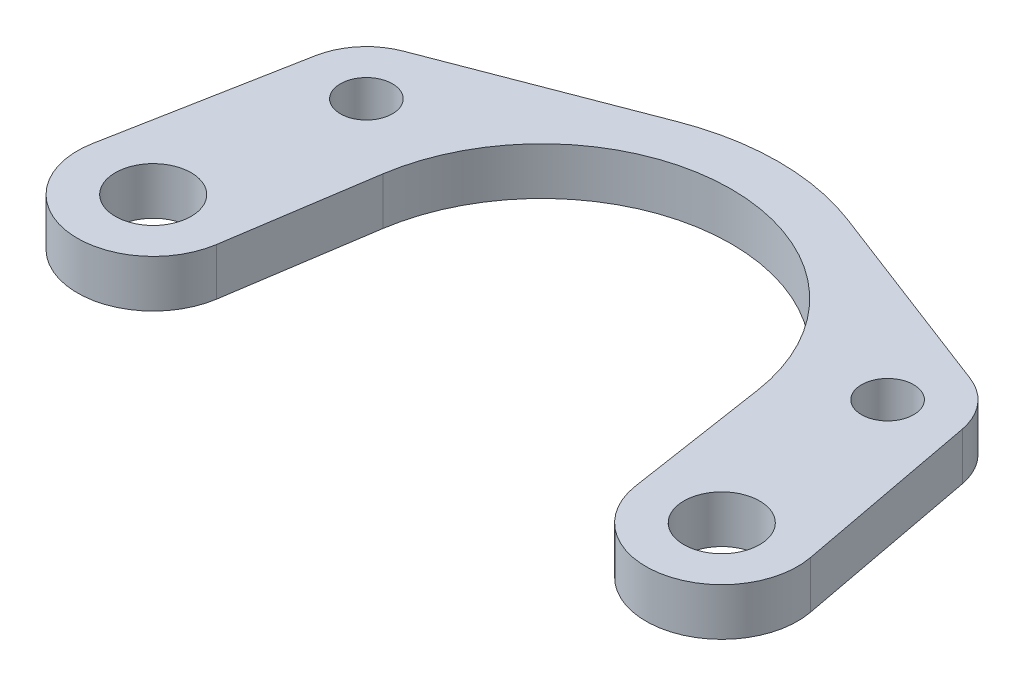
SolidWorks part; units mm, degrees
material "High-leaded brass, UNS C34200"
ref_plane "Front Plane" through (0, 0, 0) normal (0, 0, 1) x (1, 0, 0)
ref_plane "Top Plane" through (0, 0, 0) normal (0, 1, 0) x (1, 0, 0)
ref_plane "Right Plane" through (0, 0, 0) normal (1, 0, 0) x (0, 0, -1)
sketch "Sketch1" plane through (0, 0, 0) normal (0, 1, 0) x (1, 0, 0)
  line L0 (0, 25.4) -> (0, -25.4) construction
  line L1 (48.084, -12.087) -> (43.349, 13.0188)
  line L2 (28.056, -15.5009) -> (25.11, 3.8273)
  line L3 (11.3685, 29.6449) -> (37.9945, 19.4341)
  line L4 (-48.084, -12.087) -> (-43.349, 13.0188)
  line L5 (-11.3685, 29.6449) -> (-37.9945, 19.4341)
  line L6 (-28.056, -15.5009) -> (-25.11, 3.8273)
  arc A0 (25.11, 3.8273) -> (-25.11, 3.8273) centre (0, 0) ccw
  circle A1 centre (38.1, -13.97) radius 5.08
  arc A3 (28.056, -15.5009) -> (48.084, -12.087) centre (38.1, -13.97) ccw
  circle A4 centre (34.925, 11.43) radius 3.4925
  arc A5 (43.349, 13.0188) -> (37.9945, 19.4341) centre (34.925, 11.43) ccw
  circle A6 centre (-34.925, 11.43) radius 3.4925
  circle A8 centre (-38.1, -13.97) radius 5.08
  arc A9 (-28.056, -15.5009) -> (-48.084, -12.087) centre (-38.1, -13.97) cw
  arc A10 (-43.349, 13.0188) -> (-37.9945, 19.4341) centre (-34.925, 11.43) cw
  arc A12 (11.3685, 29.6449) -> (-11.3685, 29.6449) centre (0, 0) ccw
  circle A13 centre (34.925, 11.43) radius 8.5725 construction
  circle A14 centre (38.1, -13.97) radius 10.16 construction
  point P13 (0, 31.75)
  dimension "D2" = 10.16
  dimension "D3" = 50.8
  dimension "D4" = 6.985
  dimension "D8" = 6.35
  dimension "D9" = 5.08
  dimension "D10" = 5.08
  dimension "D1" = 76.2
  dimension "D5" = 69.85
  dimension "D6" = 25.4
  dimension "D7" = 20.32
extrude "Boss-Extrude1" add sketch "Sketch1" along normal blind 6.35
